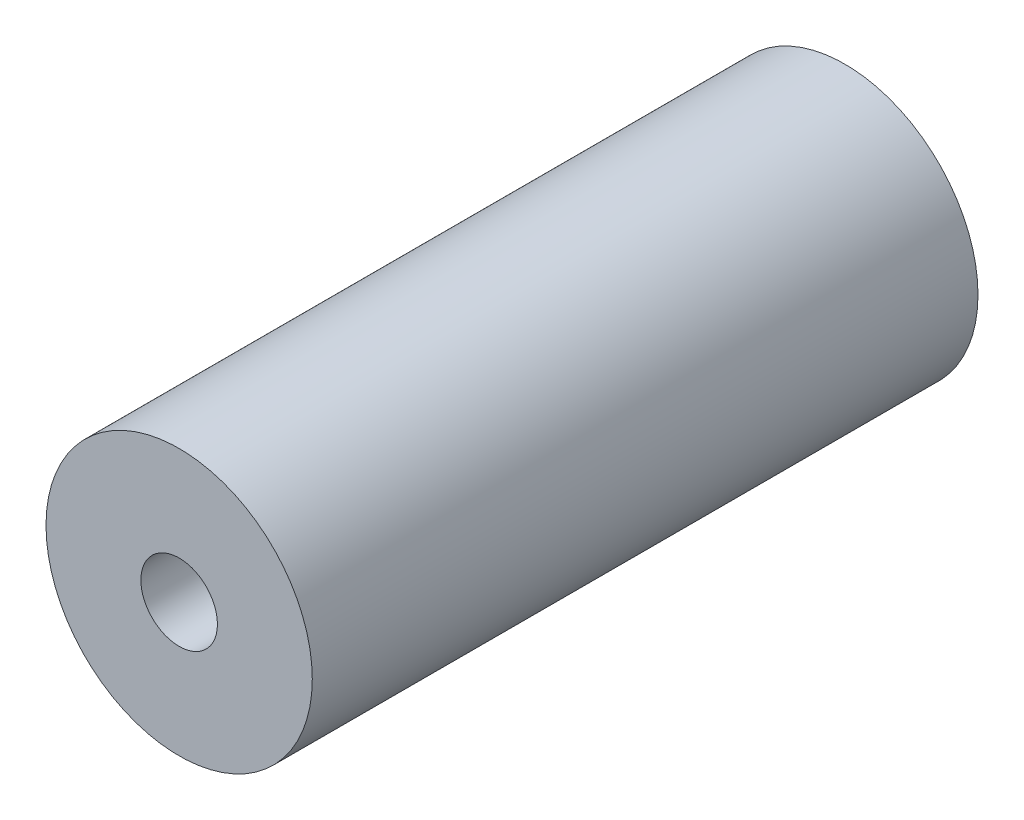
SolidWorks part; units mm, degrees
ref_plane "Front Plane" through (0, 0, 0) normal (0, 0, 1) x (1, 0, 0)
ref_plane "Top Plane" through (0, 0, 0) normal (0, 1, 0) x (1, 0, 0)
ref_plane "Right Plane" through (0, 0, 0) normal (1, 0, 0) x (0, 0, -1)
sketch "Sketch1" plane through (0, 0, 0) normal (0, 0, 1) x (1, 0, 0)
  circle A0 centre (0, 0) radius 4
  circle A1 centre (0, 0) radius 1.15
  dimension "D1" = 2.3
  dimension "D2" = 8
extrude "Boss-Extrude1" add sketch "Sketch1" along normal blind 20
sketch "Sketch2" plane through (0, 0, 0) normal (0, 1, 0) x (1, 0, 0)
  circle A0 centre (0, -8.5) radius 1.25
  dimension "D1" = 2.5
  dimension "D2" = 8.5
extrude "Cut-Extrude1" cut sketch "Sketch2" against normal blind 10
